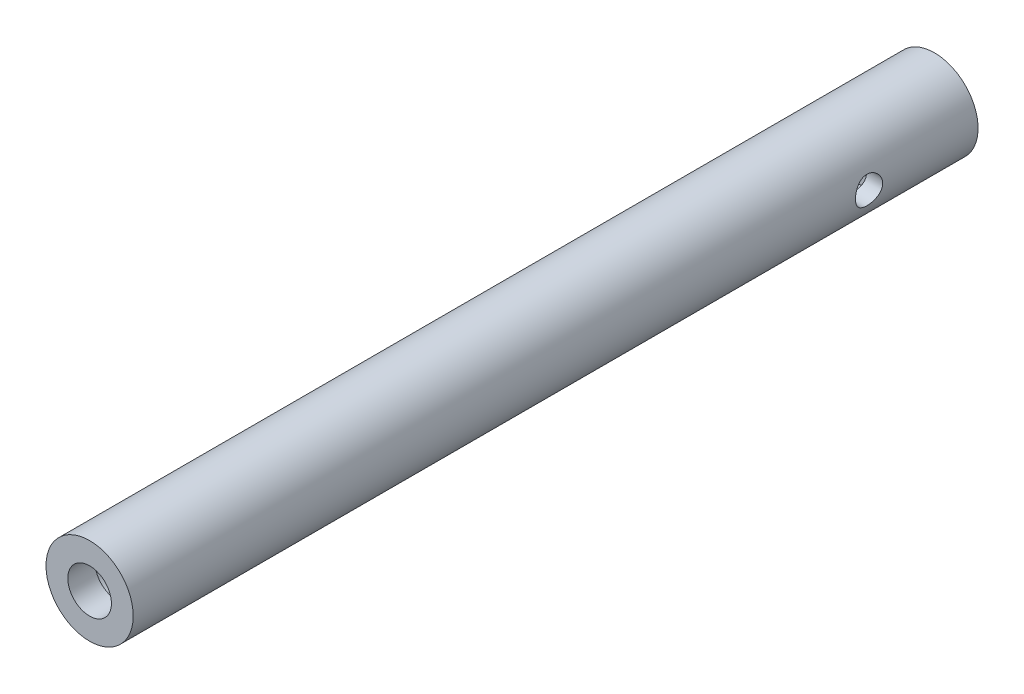
SolidWorks part; units mm, degrees
ref_plane "Front Plane" through (0, 0, 0) normal (0, 0, 1) x (1, 0, 0)
ref_plane "Top Plane" through (0, 0, 0) normal (0, 1, 0) x (1, 0, 0)
ref_plane "Right Plane" through (0, 0, 0) normal (1, 0, 0) x (0, 0, -1)
sketch "Sketch1" plane through (0, 0, 0) normal (0, 0, 1) x (1, 0, 0)
  circle A0 centre (0, 0) radius 8
  dimension "D1" = 16
extrude "Boss-Extrude1" add sketch "Sketch1" along normal blind 150
sketch "Sketch2" plane through (0, 0, 150) normal (0, 0, 1) x (1, 0, 0)
  circle A0 centre (0, 0) radius 4
  dimension "D1" = 8
extrude "Cut-Extrude1" cut sketch "Sketch2" against normal blind 5
sketch "Sketch3" plane through (0, 0, 145) normal (0, 0, 1) x (1, 0, 0)
  circle A0 centre (0, 0) radius 5
  dimension "D1" = 10
extrude "Cut-Extrude2" cut sketch "Sketch3" against normal blind 135
sketch "Sketch4" plane through (0, 0, 0) normal (1, 0, 0) x (0, 0, -1)
  line L0 (-10, 0) -> (-15, 0) construction
  line L1 (-10, 5) -> (-10, -5) construction
  circle A0 centre (-15, 0) radius 2.5
  dimension "D2" = 5
  dimension "D1" = 5
extrude "Cut-Extrude3" cut sketch "Sketch4" against normal through all and the other way through all
sketch3d "3DSketch1"
  line L0 (0, -4, 150) -> (0, -4, 145) construction
  circle A0 centre (0, 0, 150) radius 4 construction
  circle A1 centre (0, 0, 145) radius 4 construction
  point P4 (0, 0, 154)
  point P7 (0, 0, 141)
sketch "Sketch5" plane through (0, 0, 0) normal (0, 0, -1) x (-1, 0, 0)
  circle A0 centre (0, 0) radius 8
extrude "Boss-Extrude2" add sketch "Sketch5" along normal blind 5
sketch "Sketch6" plane through (0, 0, -5) normal (0, 0, -1) x (-1, 0, 0)
  circle A0 centre (0, 0) radius 5
  dimension "D1" = 10
extrude "Cut-Extrude4" cut sketch "Sketch6" against normal blind 2
sketch "Sketch7" plane through (0, 0, -3) normal (0, 0, -1) x (-1, 0, 0)
  circle A0 centre (0, 0) radius 7
  dimension "D1" = 14
extrude "Cut-Extrude5" cut sketch "Sketch7" against normal blind 2
